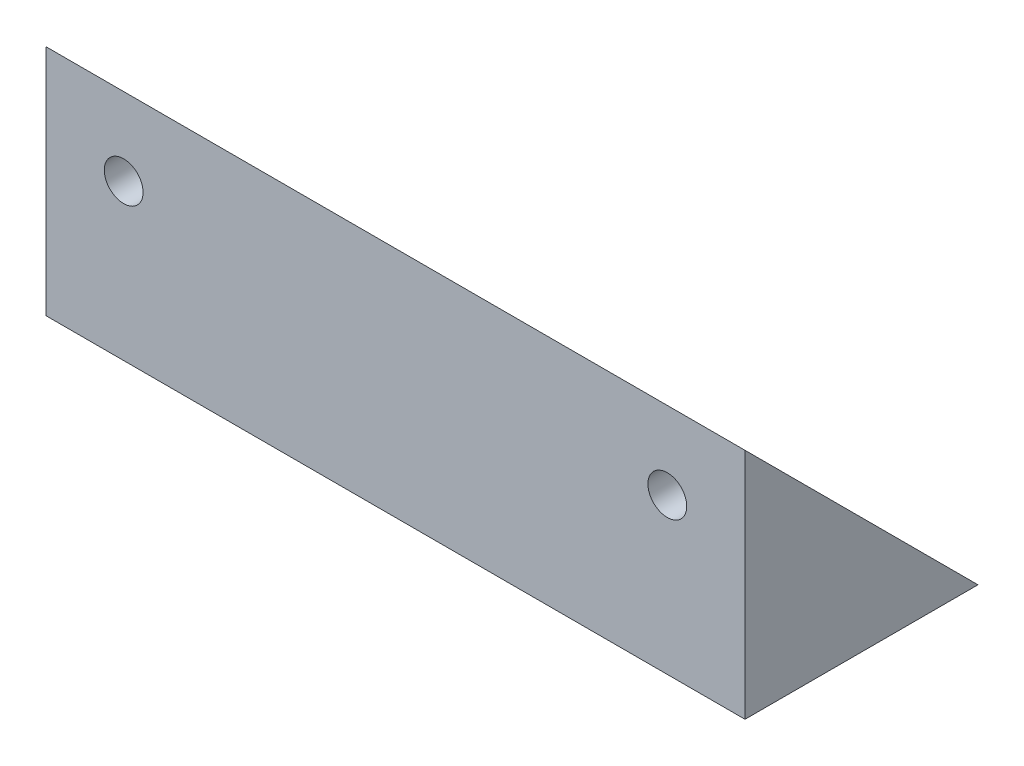
SolidWorks part; units mm, degrees
ref_plane "Front Plane" through (0, 0, 0) normal (0, 0, 1) x (1, 0, 0)
ref_plane "Top Plane" through (0, 0, 0) normal (0, 1, 0) x (1, 0, 0)
ref_plane "Right Plane" through (0, 0, 0) normal (1, 0, 0) x (0, 0, -1)
sketch "Sketch1" plane through (0, 0, 0) normal (1, 0, 0) x (0, 0, -1)
  line L0 (0, 0) -> (0, 30)
  line L1 (0, 30) -> (30, 0)
  line L2 (30, 0) -> (0, 0)
  dimension "D1" = 30
extrude "Boss-Extrude1" add sketch "Sketch1" along normal mid plane 90
sketch "Sketch2" plane through (0, 0, 0) normal (0, 0, 1) x (1, 0, 0)
  line L0 (45, 30) -> (-45, 30) construction
  line L1 (-41, 30) -> (-29, 30)
  line L2 (-41, 30) -> (-41, 10)
  line L3 (-41, 10) -> (-29, 10)
  line L4 (-29, 30) -> (-29, 10)
  line L5 (45, 0) -> (-45, 0) construction
  line L6 (28, 30) -> (40, 30)
  line L7 (28, 30) -> (28, 10)
  line L8 (28, 10) -> (40, 10)
  line L9 (40, 30) -> (40, 10)
  line L10 (-45, 30) -> (-45, 0) construction
  line L11 (45, 30) -> (45, 0) construction
  point P16 (-28.7372, 10)
  dimension "D1" = 10
  dimension "D2" = 4
  dimension "D3" = 5
  dimension "D4" = 12
extrude "Cut-Extrude1" cut sketch "Sketch2" against normal through all from offset 5 offset against normal yes
sketch "Sketch3" plane through (0, 0, 0) normal (0, 0, 1) x (1, 0, 0)
  line L0 (-35, 20) -> (35, 20) construction
  line L1 (45, 30) -> (-45, 30) construction
  line L2 (-45, 30) -> (-45, 0) construction
  circle A0 centre (-35, 20) radius 2.5
  circle A1 centre (35, 20) radius 2.5
  point P4 (0, 20)
  dimension "D1" = 5
  dimension "D2" = 10
  dimension "D3" = 10
extrude "Cut-Extrude2" cut sketch "Sketch3" against normal through all
ref_plane "Plane1" through (0, 0, 0) normal (0, -0.7071, -0.7071) x (-1, 0, 0)
mirror "Mirror1" about plane through (0, 0, 0) normal (0, -0.7071, -0.7071) of "Cut-Extrude2", "Cut-Extrude1"
